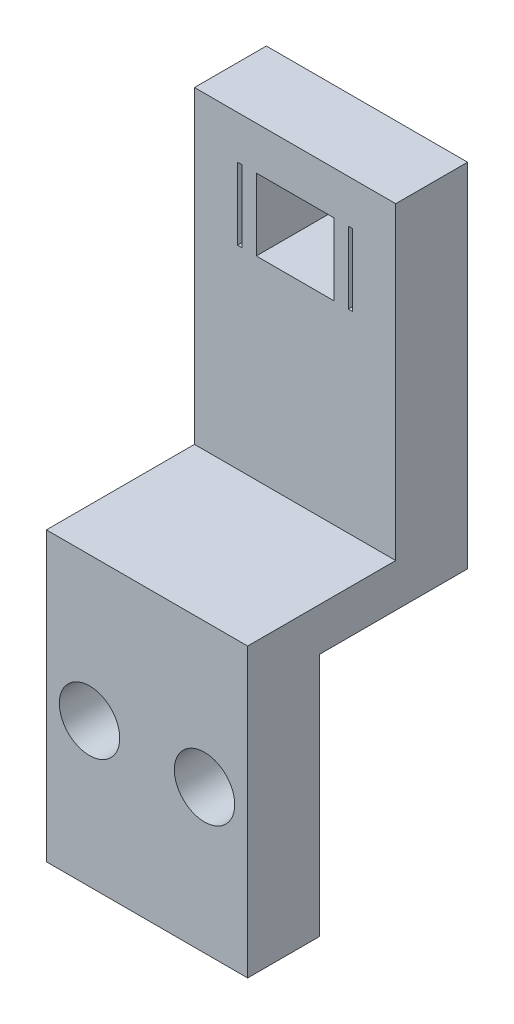
SolidWorks part; units mm, degrees
ref_plane "Front Plane" through (0, 0, 0) normal (0, 0, 1) x (1, 0, 0)
ref_plane "Top Plane" through (0, 0, 0) normal (0, 1, 0) x (1, 0, 0)
ref_plane "Right Plane" through (0, 0, 0) normal (1, 0, 0) x (0, 0, -1)
sketch "Sketch1" plane through (0, 0, 0) normal (0, 0, 1) x (1, 0, 0)
  line L0 (4.3, 38.5) -> (4.3, 33.5)
  line L1 (0, 0) -> (14, 0)
  line L2 (0, 0) -> (0, 41.5)
  line L3 (0, 41.5) -> (14, 41.5)
  line L4 (14, 0) -> (14, 41.5)
  line L9 (3, 38.5) -> (11, 38.5)
  line L10 (3, 38.5) -> (3, 33.5)
  line L11 (3, 33.5) -> (11, 33.5)
  line L12 (11, 38.5) -> (11, 33.5)
  line L13 (3.3, 38.5) -> (10.7, 38.5)
  line L14 (3.3, 38.5) -> (3.3, 33.5)
  line L15 (3.3, 33.5) -> (10.7, 33.5)
  line L16 (10.7, 38.5) -> (10.7, 33.5)
  line L17 (9.7, 38.5) -> (9.7, 33.5)
  circle A0 centre (3, 10) radius 2.1
  circle A1 centre (11, 10) radius 2.1
  dimension "D7" = 4.2
  dimension "D8" = 10
  dimension "D9" = 10
  dimension "D11" = 3
  dimension "D1" = 14
  dimension "D2" = 41.5
  dimension "D3" = 8
  dimension "D4" = 5
  dimension "D5" = 38.5
  dimension "D6" = 3
  dimension "D10" = 3
  dimension "D12" = 0.3
  dimension "D13" = 0.3
  dimension "D14" = 1
  dimension "D15" = 1
extrude "Boss-Extrude3" add sketch "Sketch1" along normal blind 15.3 contours L1 L4 L3 L2 A1 A0 L9 L13 L12 L11 L15 L10 | L9 L14 L11 L0 | L13 L17 L15 L16
sketch "Sketch2" plane through (0, 0, 0) normal (-1, 0, 0) x (0, 0, 1)
  line L0 (15.3, 0) -> (15.3, 41.5) construction
  line L1 (0, 0) -> (10.3, 0)
  line L2 (0, 0) -> (0, 17)
  line L3 (0, 17) -> (10.3, 17)
  line L4 (10.3, 0) -> (10.3, 17)
  line L5 (15.3, 41.5) -> (5, 41.5)
  line L6 (15.3, 41.5) -> (15.3, 20)
  line L7 (15.3, 20) -> (5, 20)
  line L8 (5, 41.5) -> (5, 20)
  line L9 (0, 0) -> (0, 41.5) construction
  dimension "D1" = 5
  dimension "D2" = 5
  dimension "D3" = 17
  dimension "D4" = 3
extrude "Cut-Extrude1" cut sketch "Sketch2" against normal blind 21
